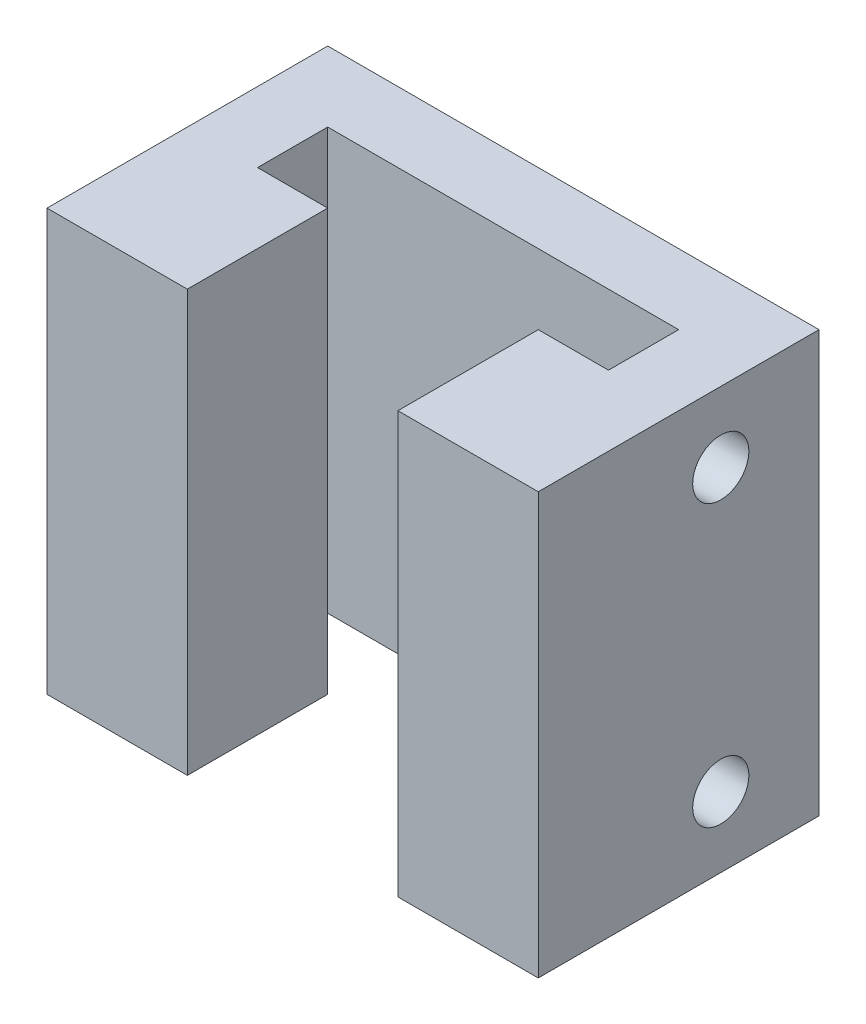
SolidWorks part; units mm, degrees
ref_plane "Front Plane" through (0, 0, 0) normal (0, 0, 1) x (1, 0, 0)
ref_plane "Top Plane" through (0, 0, 0) normal (0, 1, 0) x (1, 0, 0)
ref_plane "Right Plane" through (0, 0, 0) normal (1, 0, 0) x (0, 0, -1)
sketch "Sketch1" plane through (0, 0, 0) normal (0, 1, 0) x (1, 0, 0)
  line L0 (0, 0) -> (-10, 0)
  line L1 (-10, 0) -> (-10, 20)
  line L2 (-10, 20) -> (25, 20)
  line L3 (25, 20) -> (25, 0)
  line L4 (25, 0) -> (15, 0)
  line L5 (15, 0) -> (15, 10)
  line L7 (0, 10) -> (0, 0)
  line L8 (0, 10) -> (-5, 10)
  line L9 (-5, 10) -> (-5, 15)
  line L10 (-5, 15) -> (20, 15)
  line L11 (20, 15) -> (20, 10)
  line L12 (20, 10) -> (15, 10)
  dimension "D1" = 5
  dimension "D2" = 5
  dimension "D3" = 5
  dimension "D4" = 10
  dimension "D5" = 20
  dimension "D6" = 25
  dimension "D7" = 5
extrude "Boss-Extrude1" add sketch "Sketch1" along normal blind 30
sketch "Sketch2" plane through (-10, 0, 0) normal (-1, 0, 0) x (0, 0, 1)
  line L0 (-20, 0) -> (0, 0) construction
  line L1 (-20, 30) -> (-9, 30) construction
  line L2 (-20, 30) -> (-20, 0) construction
  line L3 (-20, 0) -> (-9, 0) construction
  line L4 (-9, 30) -> (-9, 0) construction
  circle A0 centre (-13, 25) radius 2
  circle A1 centre (-13, 5) radius 2
  dimension "D3" = 5
  dimension "D4" = 4
  dimension "D5" = 4
  dimension "D1" = 11
  dimension "D2" = 20
extrude "Cut-Extrude1" cut sketch "Sketch2" along normal blind 3 from surface at -35 starting at face at (25, 15, -10)
sketch "Sketch3" plane through (-10, 0, 0) normal (-1, 0, 0) x (0, 0, 1)
  circle A0 centre (-13, 25) radius 2
  circle A1 centre (-13, 5) radius 2
  dimension "D1" = 4
extrude "Cut-Extrude2" cut sketch "Sketch3" against normal blind 3
